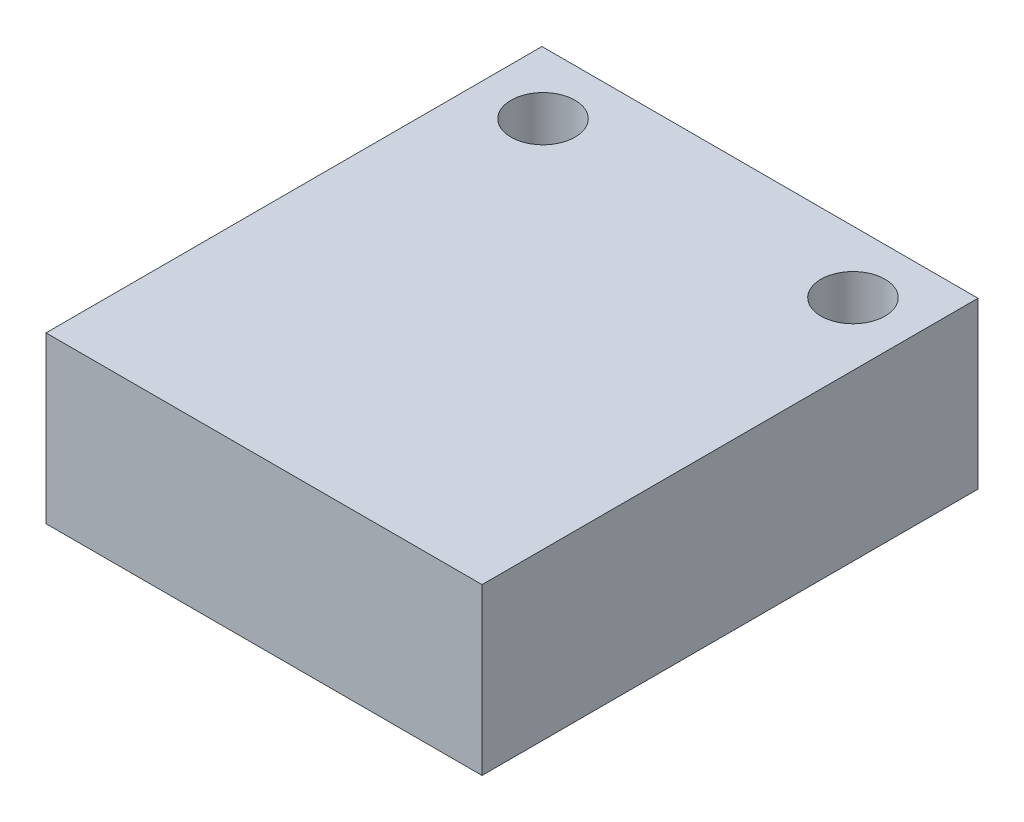
SolidWorks part; units mm, degrees
ref_plane "前视基准面" through (0, 0, 0) normal (0, 0, 1) x (1, 0, 0)
ref_plane "上视基准面" through (0, 0, 0) normal (0, 1, 0) x (1, 0, 0)
ref_plane "右视基准面" through (0, 0, 0) normal (1, 0, 0) x (0, 0, -1)
sketch "草图1" plane through (0, 0, 0) normal (0, 1, 0) x (1, 0, 0)
  line L1 (-10.55, 12) -> (10.55, 12)
  line L2 (-10.55, 12) -> (-10.55, -12)
  line L3 (-10.55, -12) -> (10.55, -12)
  line L4 (10.55, 12) -> (10.55, -12)
  line L5 (-10.55, 12) -> (10.55, -12) construction
  line L6 (-10.55, -12) -> (10.55, 12) construction
  point P0 (0, 0)
  dimension "D1" = 21.1
  dimension "D2" = 24
extrude "凸台-拉伸1" add sketch "草图1" along normal blind 8
sketch "草图2" plane through (0, 8, 0) normal (0, 1, 0) x (1, 0, 0)
  line L0 (0, 12) -> (0, -12) construction
  line L1 (10.55, 12) -> (-10.55, 12) construction
  line L2 (-10.55, -12) -> (10.55, -12) construction
  circle A0 centre (-7.5, 9) radius 1.55
  circle A1 centre (7.5, 9) radius 1.55
  dimension "D1" = 3.1
  dimension "D2" = 7.5
  dimension "D3" = 3
extrude "切除-拉伸1" cut sketch "草图2" against normal blind 8
